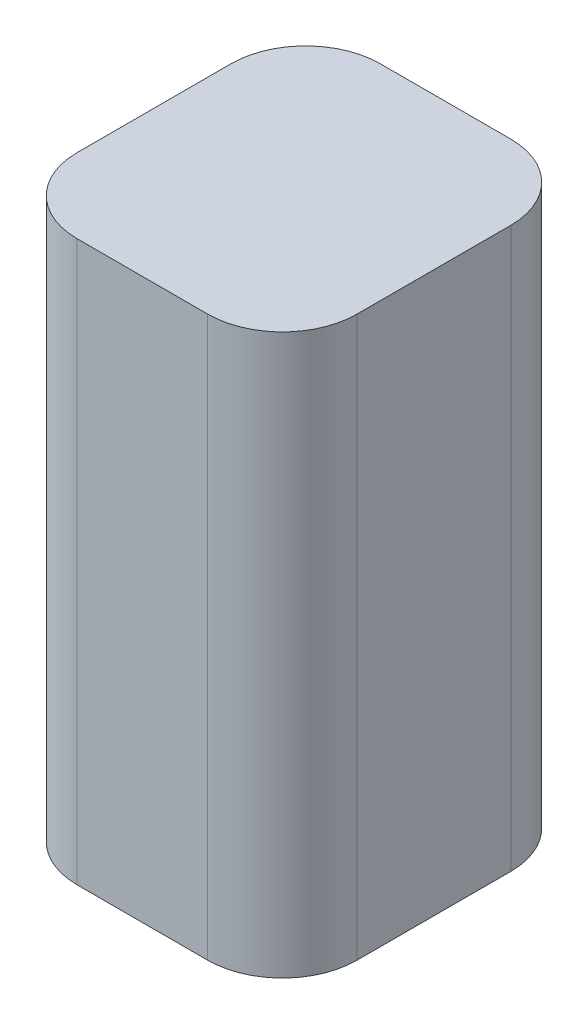
SolidWorks part; units mm, degrees
ref_plane "Front Plane" through (0, 0, 0) normal (0, 0, 1) x (1, 0, 0)
ref_plane "Top Plane" through (0, 0, 0) normal (0, 1, 0) x (1, 0, 0)
ref_plane "Right Plane" through (0, 0, 0) normal (1, 0, 0) x (0, 0, -1)
sketch "Sketch1" plane through (0, 0, 0) normal (0, 1, 0) x (1, 0, 0)
  line L1 (-355.6, -825.5) -> (355.6, -825.5)
  line L2 (-762, -419.1) -> (-762, 419.1)
  line L3 (-355.6, 825.5) -> (355.6, 825.5)
  line L4 (762, -419.1) -> (762, 419.1)
  line L5 (-762, -825.5) -> (762, 825.5) construction
  line L6 (-762, 825.5) -> (762, -825.5) construction
  arc A0 (-762, -419.1) -> (-355.6, -825.5) centre (-355.6, -419.1) ccw
  arc A1 (355.6, -825.5) -> (762, -419.1) centre (355.6, -419.1) ccw
  arc A2 (762, 419.1) -> (355.6, 825.5) centre (355.6, 419.1) ccw
  arc A3 (-355.6, 825.5) -> (-762, 419.1) centre (-355.6, 419.1) ccw
  point P0 (0, 0)
  dimension "D1" = 406.4
extrude "Boss-Extrude1" add sketch "Sketch1" along normal blind 3048
